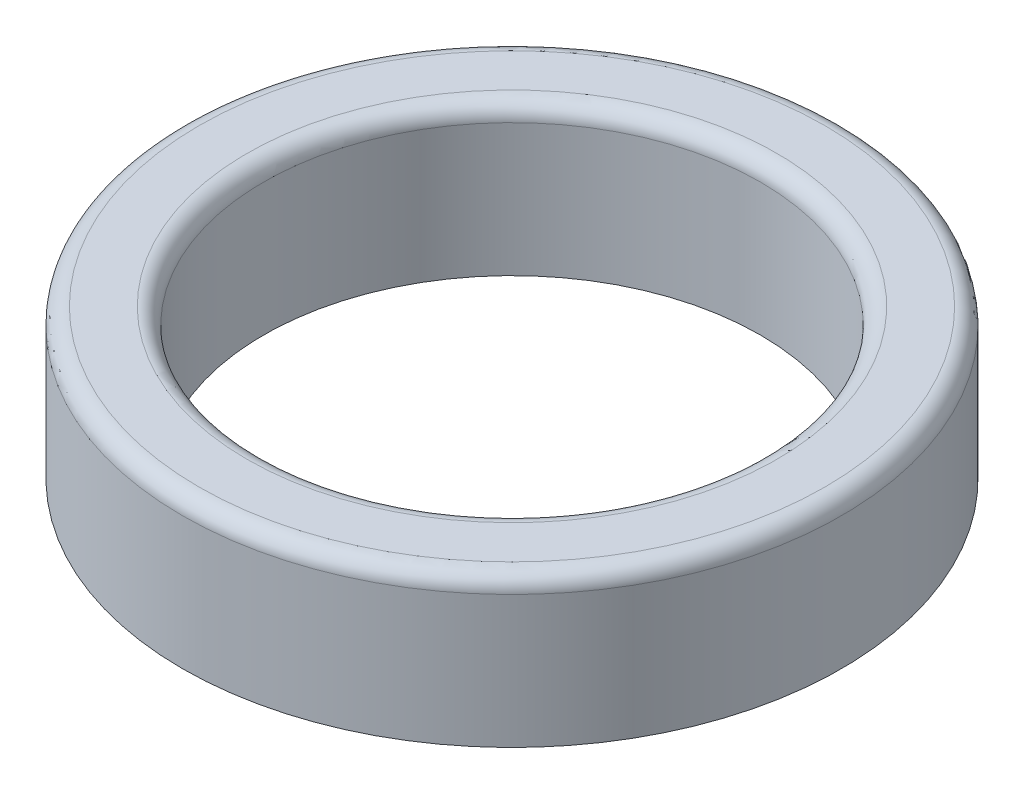
SolidWorks part; units mm, degrees
ref_plane "Front Plane" through (0, 0, 0) normal (0, 0, 1) x (1, 0, 0)
ref_plane "Top Plane" through (0, 0, 0) normal (0, 1, 0) x (1, 0, 0)
ref_plane "Right Plane" through (0, 0, 0) normal (1, 0, 0) x (0, 0, -1)
sketch "Sketch1" plane through (0, 0, 0) normal (0, 1, 0) x (1, 0, 0)
  circle A0 centre (0, 0) radius 15
  circle A1 centre (0, 0) radius 19.9
  dimension "D1" = 30
  dimension "D2" = 39.8
extrude "Boss-Extrude2" add sketch "Sketch1" along normal blind 9
fillet "Fillet1" radius 1 2 edges at (0, 9, 15) (0, 9, 19.9)
